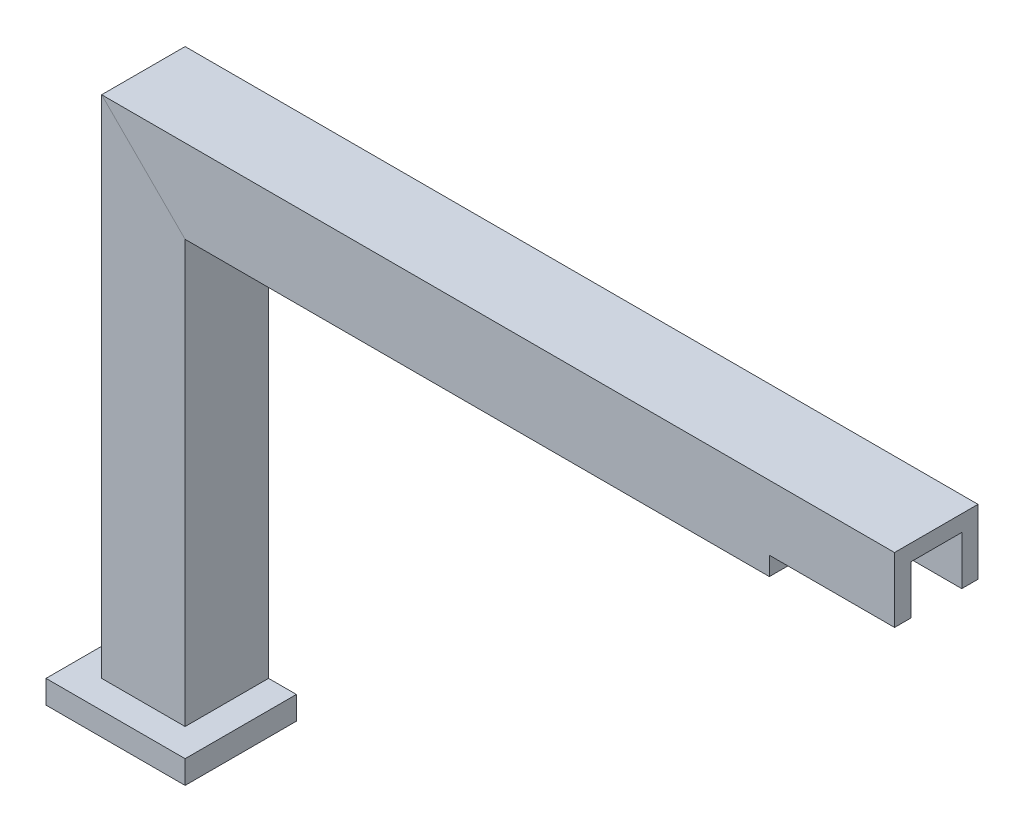
SolidWorks part; units mm, degrees
ref_plane "Front Plane" through (0, 0, 0) normal (0, 0, 1) x (1, 0, 0)
ref_plane "Top Plane" through (0, 0, 0) normal (0, 1, 0) x (1, 0, 0)
ref_plane "Right Plane" through (0, 0, 0) normal (1, 0, 0) x (0, 0, -1)
sketch "Sketch1" plane through (0, 0, 0) normal (0, 0, 1) x (1, 0, 0)
  line L0 (0, 0) -> (0, 100)
  line L1 (0, 100) -> (320, 100)
  line L2 (320, 100) -> (320, 0)
  line L3 (320, 0) -> (0, 0) construction
  dimension "D1" = 320
  dimension "D2" = 100
sketch "Sketch2" plane through (0, 0, 0) normal (0, 1, 0) x (1, 0, 0)
  line L1 (5.5, -5.5) -> (-5.5, -5.5)
  line L2 (5.5, -5.5) -> (5.5, 5.5)
  line L3 (5.5, 5.5) -> (-5.5, 5.5)
  line L4 (-5.5, -5.5) -> (-5.5, 5.5)
  line L5 (5.5, -5.5) -> (-5.5, 5.5) construction
  line L6 (5.5, 5.5) -> (-5.5, -5.5) construction
  line L7 (9, -9) -> (-9, -9)
  line L8 (9, -9) -> (9, 9)
  line L9 (9, 9) -> (-9, 9)
  line L10 (-9, -9) -> (-9, 9)
  line L11 (9, -9) -> (-9, 9) construction
  line L12 (9, 9) -> (-9, -9) construction
  point P0 (0, 0)
  point P6 (0, 0)
  dimension "D1" = 11
  dimension "D2" = 11
  dimension "D3" = 18
  dimension "D4" = 18
sweep "Sweep2" add profiles "Sketch2" path "Sketch1"
sketch "Sketch3" plane through (0, 0, 0) normal (0, 1, 0) x (1, 0, 0)
  line L1 (-15, 15) -> (15, 15)
  line L2 (-15, 15) -> (-15, -15)
  line L3 (-15, -15) -> (15, -15)
  line L4 (15, 15) -> (15, -15)
  line L5 (-15, 15) -> (15, -15) construction
  line L6 (-15, -15) -> (15, 15) construction
  line L7 (303.0092, 17.3683) -> (336.9908, 17.3683)
  line L8 (303.0092, 17.3683) -> (303.0092, -17.3683)
  line L9 (303.0092, -17.3683) -> (336.9908, -17.3683)
  line L10 (336.9908, 17.3683) -> (336.9908, -17.3683)
  line L11 (303.0092, 17.3683) -> (336.9908, -17.3683) construction
  line L12 (303.0092, -17.3683) -> (336.9908, 17.3683) construction
  point P0 (0, 0)
  point P5 (320, 0)
  dimension "D1" = 30
  dimension "D2" = 30
extrude "Boss-Extrude1" add sketch "Sketch3" against normal blind 5
sketch "Sketch4" plane through (0, 91, 0) normal (0, -1, 0) x (1, 0, 0)
  line L0 (0, 0) -> (320, 0) construction
  line L1 (185, -9) -> (135, -9)
  line L2 (185, -9) -> (185, 9)
  line L3 (185, 9) -> (135, 9)
  line L4 (135, -9) -> (135, 9)
  line L5 (185, -9) -> (135, 9) construction
  line L6 (185, 9) -> (135, -9) construction
  line L7 (9, 9) -> (311, 9) construction
  point P0 (160, 0)
  dimension "D1" = 50
extrude "Cut-Extrude1" cut sketch "Sketch4" against normal blind 4
sketch "Sketch5" plane through (336.9908, 0, 0) normal (1, 0, 0) x (0, 0, -1)
  line L1 (-17.3683, -5) -> (44.4331, -5)
  line L2 (-17.3683, -5) -> (-17.3683, 118.6208)
  line L3 (-17.3683, 118.6208) -> (44.4331, 118.6208)
  line L4 (44.4331, -5) -> (44.4331, 118.6208)
extrude "Cut-Extrude2" cut sketch "Sketch5" against normal blind 175
sketch "Sketch6" plane through (0, 0, 0) normal (0, 1, 0) x (1, 0, 0)
  line L0 (15, -15) -> (15, 15) construction
  line L1 (-15, 15) -> (15, 15)
  line L2 (-15, 15) -> (-15, 9)
  line L3 (-15, 9) -> (15, 9)
  line L4 (15, 15) -> (15, 9)
  line L5 (9, 9) -> (-9, 9) construction
extrude "Cut-Extrude3" cut sketch "Sketch6" against normal blind 10
